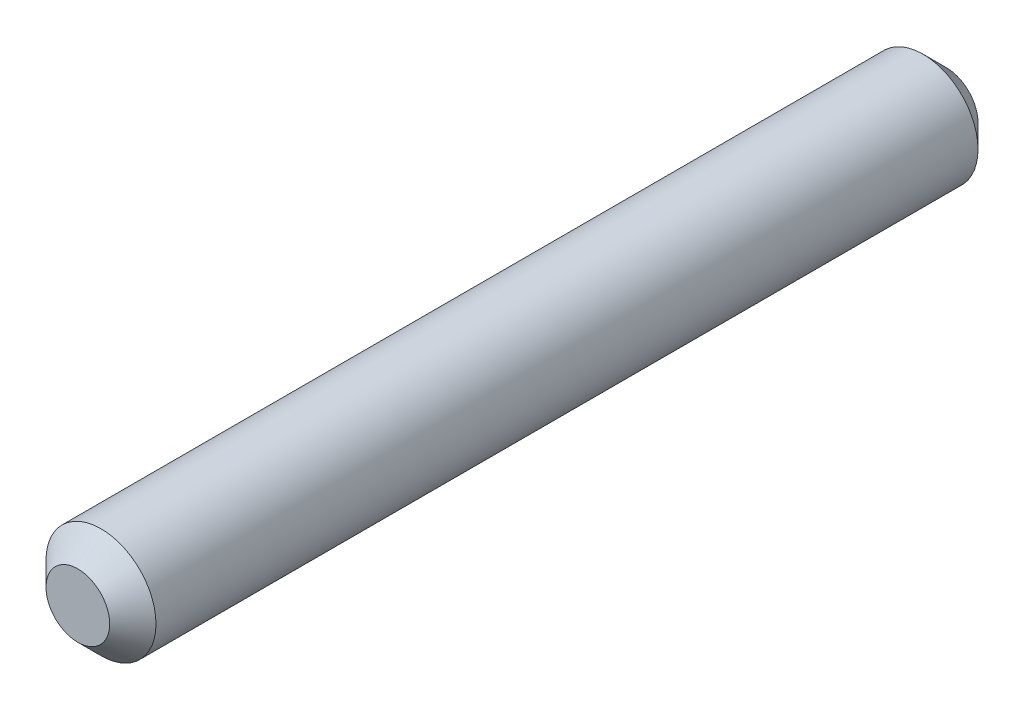
SolidWorks part; units mm, degrees
ref_plane "Front Plane" through (0, 0, 0) normal (0, 0, 1) x (1, 0, 0)
ref_plane "Top Plane" through (0, 0, 0) normal (0, 1, 0) x (1, 0, 0)
ref_plane "Right Plane" through (0, 0, 0) normal (1, 0, 0) x (0, 0, -1)
sketch "Sketch1" plane through (0, 0, 0) normal (0, 0, 1) x (1, 0, 0)
  circle A0 centre (0, 0) radius 4.75
  dimension "D1" = 9.5
extrude "Boss-Extrude1" add sketch "Sketch1" along normal blind 75
chamfer "Chamfer1" distance 2 angle 45 2 edges at (4.75, 0, 75) (4.75, 0, 0)
